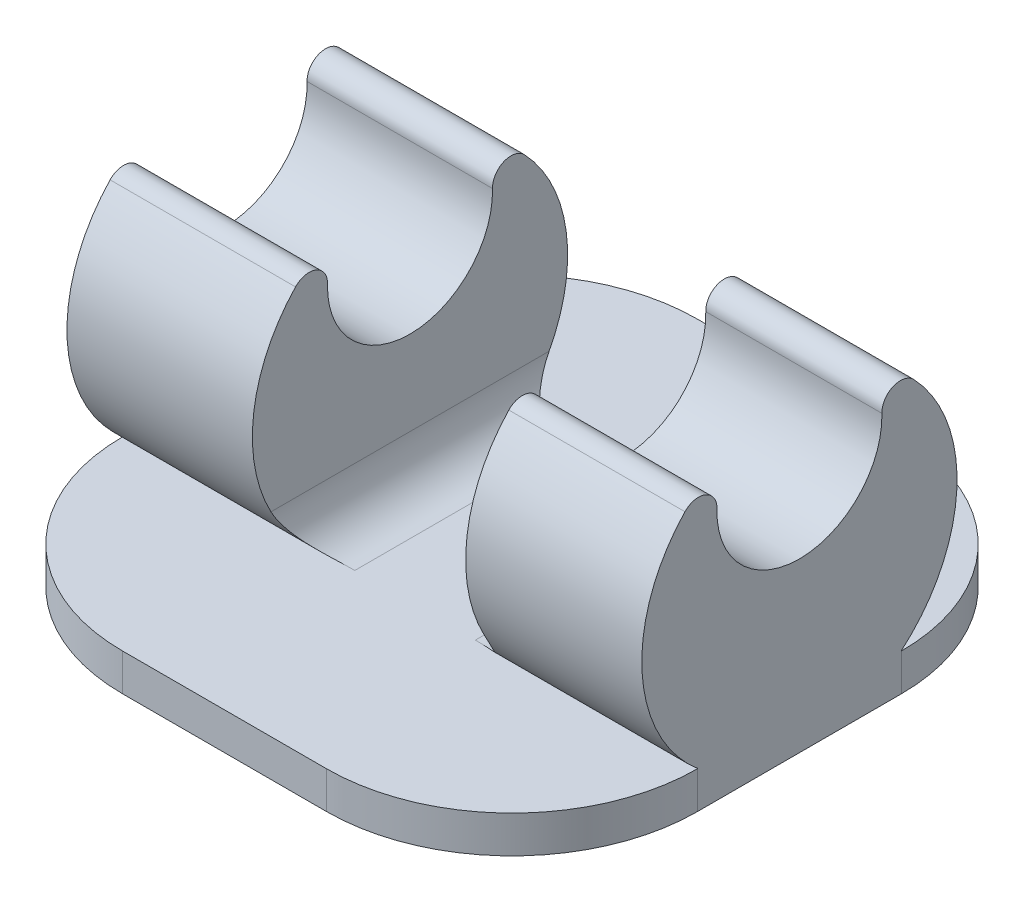
SolidWorks part; units mm, degrees
ref_plane "Front Plane" through (0, 0, 0) normal (0, 0, 1) x (1, 0, 0)
ref_plane "Top Plane" through (0, 0, 0) normal (0, 1, 0) x (1, 0, 0)
ref_plane "Right Plane" through (0, 0, 0) normal (1, 0, 0) x (0, 0, -1)
sketch "Sketch1" plane through (0, 0, 0) normal (0, 1, 0) x (1, 0, 0)
  line L2 (0, 15.5) -> (15.5, 15.5)
  line L3 (0, 15.5) -> (-15.5, 15.5)
  line L4 (-15.5, 15.5) -> (-15.5, -15.5)
  line L5 (-15.5, -15.5) -> (15.5, -15.5)
  line L6 (15.5, -15.5) -> (15.5, 15.5)
extrude "Boss-Extrude1" add sketch "Sketch1" along normal blind 2
sketch "Sketch2" plane through (15.5, 0, 0) normal (1, 0, 0) x (0, 0, -1)
  circle A0 centre (0, 8.5) radius 8.5
extrude "Boss-Extrude3" add sketch "Sketch2" against normal up to surface (31 mm away) up to face at (-15.5, 1, 0)
sketch "Sketch3" plane through (-15.5, 0, 0) normal (-1, 0, 0) x (0, 0, 1)
  circle A0 centre (0, 13.5) radius 4.45
extrude "Cut-Extrude1" cut sketch "Sketch3" against normal blind 33
fillet "Fillet1" radius 1 2 edges at (0, 16.2448, 3.5027) (0, 16.2448, -3.5027)
sketch "Sketch4" plane through (0, 2, 0) normal (0, 1, 0) x (1, 0, 0)
  line L1 (15.5, 15.5) -> (-15.5, 15.5) construction
  line L2 (-5.5, 15.5) -> (-5.5, -15.5)
  line L3 (-15.5, -15.5) -> (15.5, -15.5) construction
  line L4 (-5.5, -15.5) -> (6.0022, -15.5)
  line L5 (6.0022, -15.5) -> (6.0022, 15.5)
  line L6 (6.0022, 15.5) -> (-5.5, 15.5)
extrude "Cut-Extrude2" cut sketch "Sketch4" along normal blind 20
fillet "Fillet2" radius 10 4 edges at (-15.5, 1, -15.5) (-15.5, 1, 15.5) (15.5, 1, 15.5) (15.5, 1, -15.5)
fillet "Fillet3" radius 2.5 2 edges at (6.0022, 2, 0) (-5.5, 2, 0)
